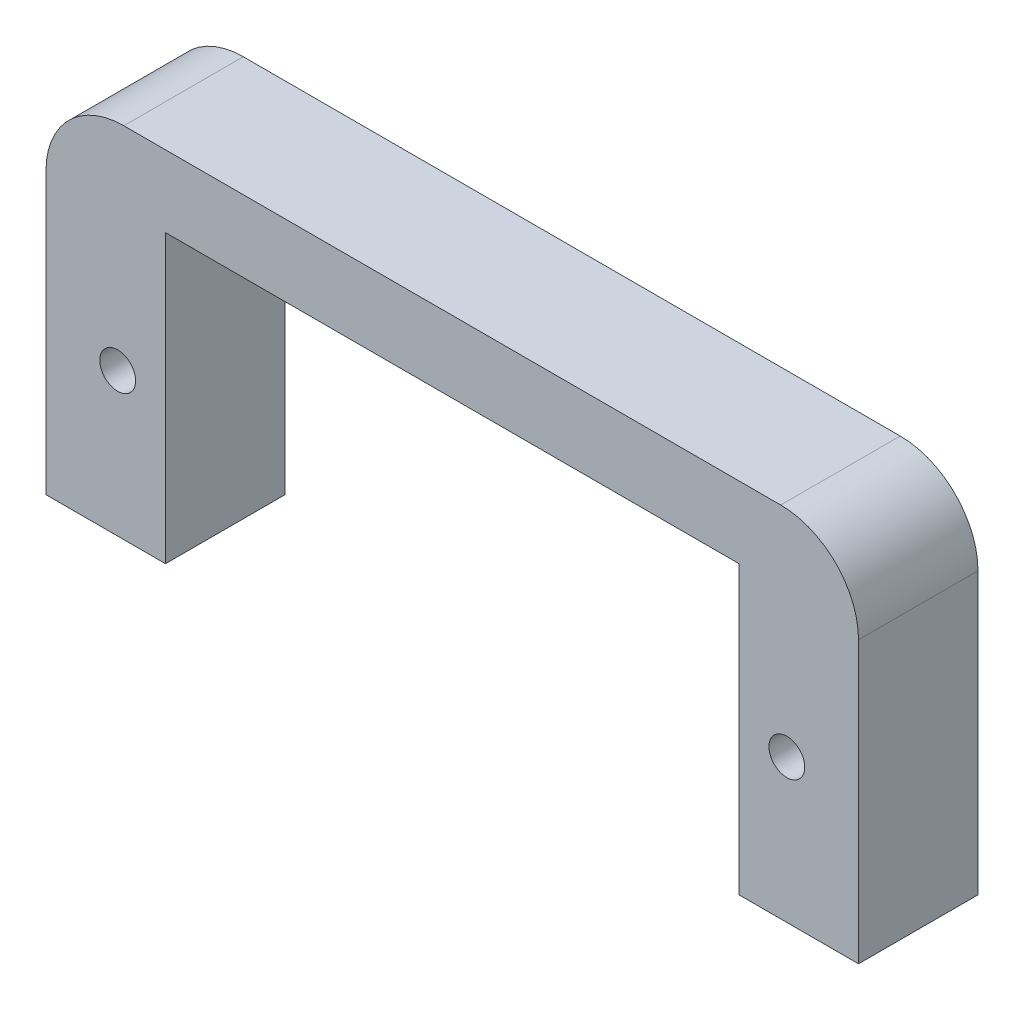
SolidWorks part; units mm, degrees
ref_plane "Alzado" through (0, 0, 0) normal (0, 0, 1) x (1, 0, 0)
ref_plane "Planta" through (0, 0, 0) normal (0, 1, 0) x (1, 0, 0)
ref_plane "Vista lateral" through (0, 0, 0) normal (1, 0, 0) x (0, 0, -1)
sketch "Croquis1" plane through (0, 0, 0) normal (0, 0, 1) x (1, 0, 0)
  line L0 (0, 0) -> (0, 50000) construction
  line L1 (-12, 6) -> (12, 6)
  line L2 (-12, 6) -> (-12, -6)
  line L3 (-12, -6) -> (12, -6) construction
  line L4 (12, 6) -> (12, -6)
  line L5 (-12, 6) -> (12, -6) construction
  line L6 (-12, -6) -> (12, 6) construction
  line L7 (-12, -6) -> (-17, -6)
  line L8 (-17, -6) -> (-17, 5.7445)
  line L9 (-13.7445, 9) -> (13.7445, 9)
  line L11 (17, -6) -> (17, 5.7445)
  line L12 (12, -6) -> (17, -6)
  circle A0 centre (-14, 0) radius 0.75
  arc A2 (-17, 5.7445) -> (-13.7445, 9) centre (-13.7445, 5.7445) cw
  arc A3 (17, 5.7445) -> (13.7445, 9) centre (13.7445, 5.7445) ccw
  circle A4 centre (14, 0) radius 0.75
  point P0 (0, 0)
  point P16 (0, 9)
  dimension "D1" = 1.5
  dimension "D2" = 12
  dimension "D3" = 24
  dimension "D4" = 14
  dimension "D5" = 3
  dimension "D6" = 5
extrude "Saliente-Extruir1" add sketch "Croquis1" along normal mid plane 5
